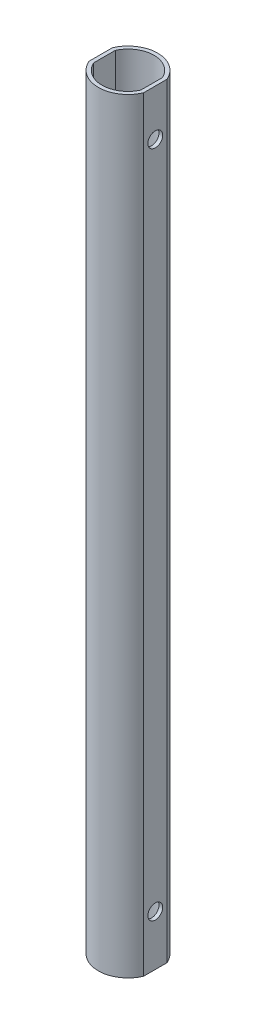
SolidWorks part; units mm, degrees
material "6061-T6 (SS)"
ref_plane "Front Plane" through (0, 0, 0) normal (0, 0, 1) x (1, 0, 0)
ref_plane "Top Plane" through (0, 0, 0) normal (0, 1, 0) x (1, 0, 0)
ref_plane "Right Plane" through (0, 0, 0) normal (1, 0, 0) x (0, 0, -1)
sketch "Sketch1" plane through (0, 0, 0) normal (0, 1, 0) x (1, 0, 0)
  line L0 (10.0868, 4.663) -> (10.0868, -4.663)
  line L1 (11.6743, -5) -> (11.6743, 5)
  line L4 (0, 12.7) -> (0, -12.7) construction
  line L5 (10.0868, 4.663) -> (-10.0868, 4.663) construction
  line L6 (10.0868, -4.663) -> (-10.0868, -4.663) construction
  line L7 (-10.0868, 4.663) -> (-10.0868, -4.663)
  line L8 (11.6743, 5) -> (-11.6743, 5) construction
  line L9 (11.6743, -5) -> (-11.6743, -5) construction
  line L10 (-11.6743, 5) -> (-11.6743, -5)
  arc A0 (11.6743, 5) -> (-11.6743, 5) centre (0, 0) ccw
  arc A1 (10.0868, 4.663) -> (-10.0868, 4.663) centre (0, 0) ccw
  arc A2 (-10.0868, -4.663) -> (10.0868, -4.663) centre (0, 0) ccw
  arc A3 (-11.6743, -5) -> (11.6743, -5) centre (0, 0) ccw
  dimension "D1" = 25.4
  dimension "D2" = 9.326
  dimension "D3" = 10
  dimension "D4" = 1.5875
extrude "Boss-Extrude1" add sketch "Sketch1" along normal blind 327.29
ref_plane "Plane1" through (0, 163.645, 0) normal (0, -1, 0) x (-1, 0, 0)
sketch "Sketch2" plane through (11.6743, 0, 0) normal (1, 0, 0) x (0, 0, -1)
  line L0 (-5, 0) -> (5, 0) construction
  line L1 (-5, 327.29) -> (5, 327.29) construction
  line L2 (5, 327.29) -> (5, 0) construction
  circle A0 centre (0, 21.5) radius 3.175
  circle A1 centre (0, 307.54) radius 3.175
  dimension "D1" = 6.35
  dimension "D2" = 6.35
  dimension "D3" = 21.5
  dimension "D4" = 19.75
  dimension "D5" = 5
  dimension "D6" = 5
extrude "Cut-Extrude1" cut sketch "Sketch2" against normal up to surface (23.3487 mm away) up to face at (-11.6743, 163.645, 0)
